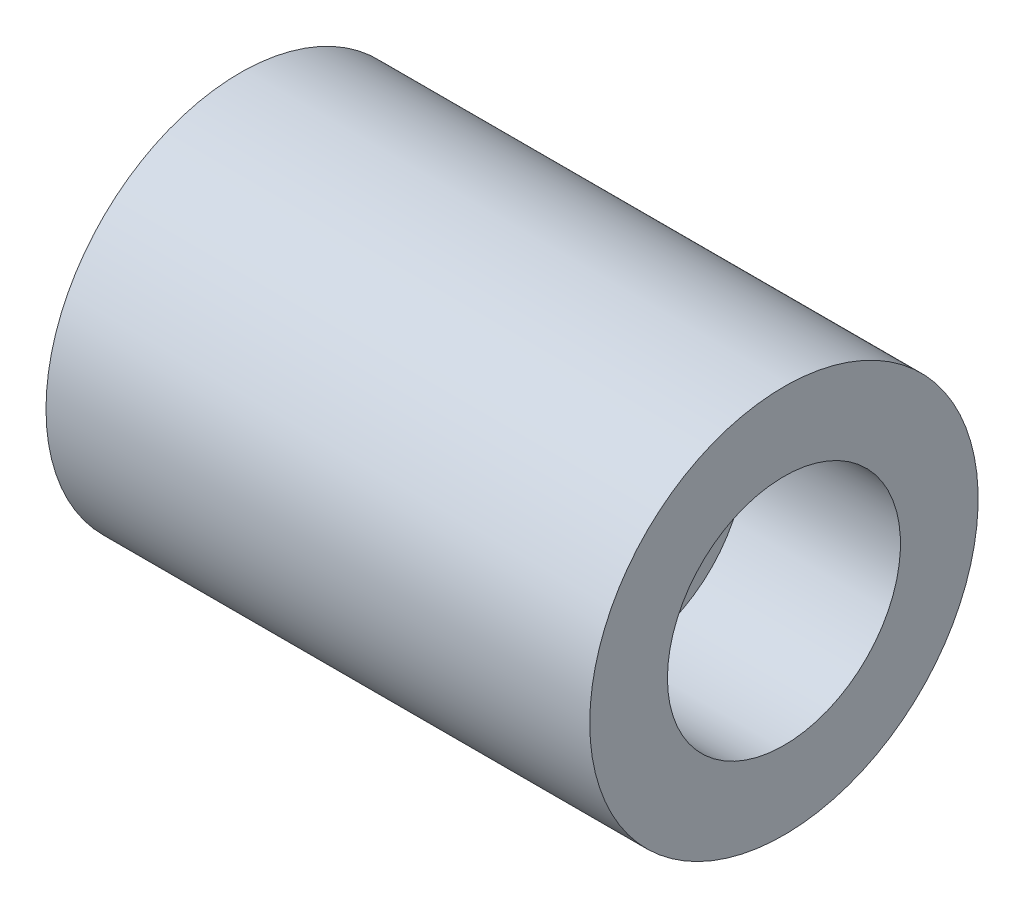
SolidWorks part; units mm, degrees
ref_plane "前基準面" through (0, 0, 0) normal (0, 0, 1) x (1, 0, 0)
ref_plane "上基準面" through (0, 0, 0) normal (0, 1, 0) x (1, 0, 0)
ref_plane "右基準面" through (0, 0, 0) normal (1, 0, 0) x (0, 0, -1)
ref_plane "平面1"
sketch "草圖1" plane through (0, 0, 0) normal (0, 0, 1) x (1, 0, 0)
  line L0 (0, 0) -> (0, 50)
  line L1 (0, 50) -> (140, 50)
  line L2 (140, 50) -> (140, 30)
  line L3 (140, 30) -> (100, 30)
  line L4 (100, 30) -> (100, 10)
  line L5 (100, 10) -> (20, 10)
  line L6 (20, 10) -> (20, 0)
  line L7 (20, 0) -> (0, 0)
  line L8 (0, 0) -> (140, 0) construction
  dimension "D1" = 50
  dimension "D2" = 140
  dimension "D3" = 120
  dimension "D4" = 10
  dimension "D5" = 80
  dimension "D6" = 20
revolve "迴轉1" add sketch "草圖1" angle 360 about L8
